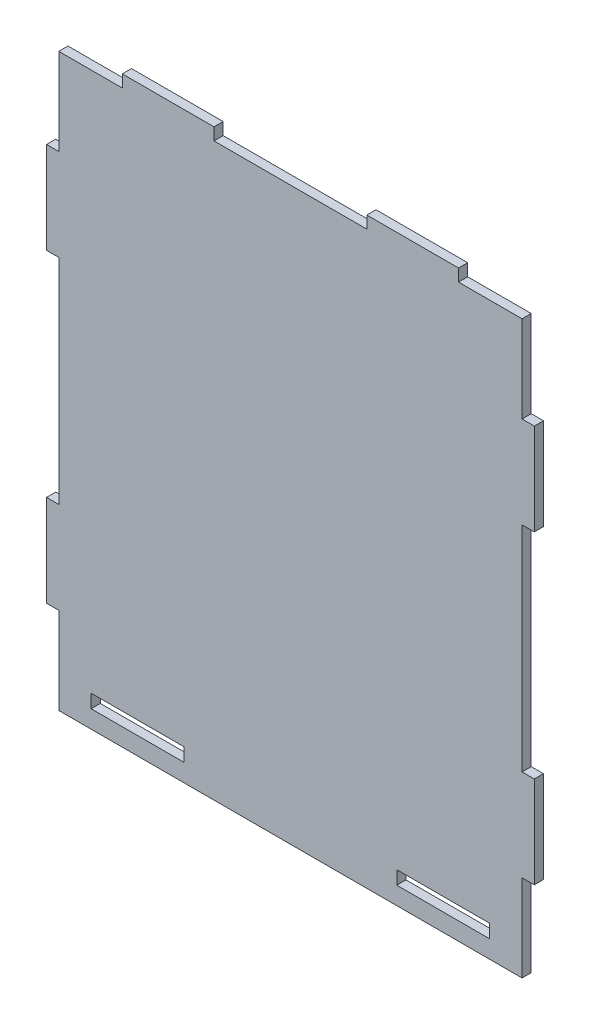
SolidWorks part; units mm, degrees
ref_plane "Спереди" through (0, 0, 0) normal (0, 0, 1) x (1, 0, 0)
ref_plane "Сверху" through (0, 0, 0) normal (0, 1, 0) x (1, 0, 0)
ref_plane "Справа" through (0, 0, 0) normal (1, 0, 0) x (0, 0, -1)
sketch "Эскиз1" plane through (0, 0, 0) normal (0, 0, 1) x (1, 0, 0)
  line L0 (-4, 143.4) -> (0, 143.4) construction
  line L1 (0, 0) -> (151.6, 0)
  line L2 (0, 0) -> (0, 186.8)
  line L3 (0, 186.8) -> (151.6, 186.8)
  line L4 (151.6, 0) -> (151.6, 186.8)
  line L5 (0, 28.4) -> (-4, 28.4)
  line L6 (0, 28.4) -> (0, 58.4)
  line L7 (0, 58.4) -> (-4, 58.4)
  line L8 (-4, 28.4) -> (-4, 58.4)
  line L9 (0, 158.4) -> (-4, 158.4)
  line L10 (0, 158.4) -> (0, 128.4)
  line L11 (0, 128.4) -> (-4, 128.4)
  line L12 (-4, 158.4) -> (-4, 128.4)
  line L13 (151.6, 158.4) -> (155.6, 158.4)
  line L14 (151.6, 158.4) -> (151.6, 128.4)
  line L15 (151.6, 128.4) -> (155.6, 128.4)
  line L16 (155.6, 158.4) -> (155.6, 128.4)
  line L17 (151.6, 58.4) -> (155.6, 58.4)
  line L18 (151.6, 58.4) -> (151.6, 28.4)
  line L19 (151.6, 28.4) -> (155.6, 28.4)
  line L20 (155.6, 58.4) -> (155.6, 28.4)
  line L21 (-4, 43.4) -> (0, 43.4) construction
  line L22 (155.6, 43.4) -> (151.6, 43.4) construction
  line L23 (155.6, 143.4) -> (151.6, 143.4) construction
  line L24 (75.8, 186.8) -> (75.8, 206.4246) construction
  line L25 (20.8, 186.8) -> (50.8, 186.8)
  line L26 (20.8, 186.8) -> (20.8, 190.8)
  line L27 (20.8, 190.8) -> (50.8, 190.8)
  line L28 (50.8, 186.8) -> (50.8, 190.8)
  line L29 (100.8, 186.8) -> (130.8, 186.8)
  line L30 (100.8, 186.8) -> (100.8, 190.8)
  line L31 (100.8, 190.8) -> (130.8, 190.8)
  line L32 (130.8, 186.8) -> (130.8, 190.8)
  line L33 (35.8, 190.8) -> (35.8, 186.8) construction
  line L34 (115.8, 190.8) -> (115.8, 186.8) construction
  line L35 (75.8, 0) -> (75.8, 24.9866) construction
  line L36 (10.6, 5.8) -> (41, 5.8)
  line L37 (10.6, 5.8) -> (10.6, 10.2)
  line L38 (10.6, 10.2) -> (41, 10.2)
  line L39 (41, 5.8) -> (41, 10.2)
  line L40 (110.6, 5.8) -> (141, 5.8)
  line L41 (110.6, 5.8) -> (110.6, 10.2)
  line L42 (110.6, 10.2) -> (141, 10.2)
  line L43 (141, 5.8) -> (141, 10.2)
  line L44 (25.8, 10.2) -> (25.8, 5.8) construction
  line L45 (125.8, 10.2) -> (125.8, 5.8) construction
  line L46 (110.6, 5.8) -> (41, 5.8) construction
  line L47 (41, 8) -> (47.917, 8) construction
  point P53 (125.8, 5.8)
  dimension "D1" = 151.6
  dimension "D2" = 186.8
  dimension "D3" = 30
  dimension "D4" = 30
  dimension "D5" = 30
  dimension "D6" = 30
  dimension "D7" = 43.4
  dimension "D8" = 100
  dimension "D9" = 100
  dimension "D10" = 4
  dimension "D11" = 4
  dimension "D12" = 4
  dimension "D13" = 4
  dimension "D14" = 30
  dimension "D15" = 4
  dimension "D16" = 30
  dimension "D17" = 4
  dimension "D18" = 40
  dimension "D19" = 40
  dimension "D20" = 30.4
  dimension "D21" = 30.4
  dimension "D22" = 4.4
  dimension "D23" = 4.4
  dimension "D24" = 50
  dimension "D25" = 50
  dimension "D26" = 8
extrude "Бобышка-Вытянуть1" add sketch "Эскиз1" along normal blind 3 contours L1 L4 L3 L2 | L8 L5 L2 L7 | L9 L12 L11 L2 | L16 L13 L4 L15 | L20 L17 L4 L19 | L3 L28 L27 L26 | L3 L32 L31 L30
